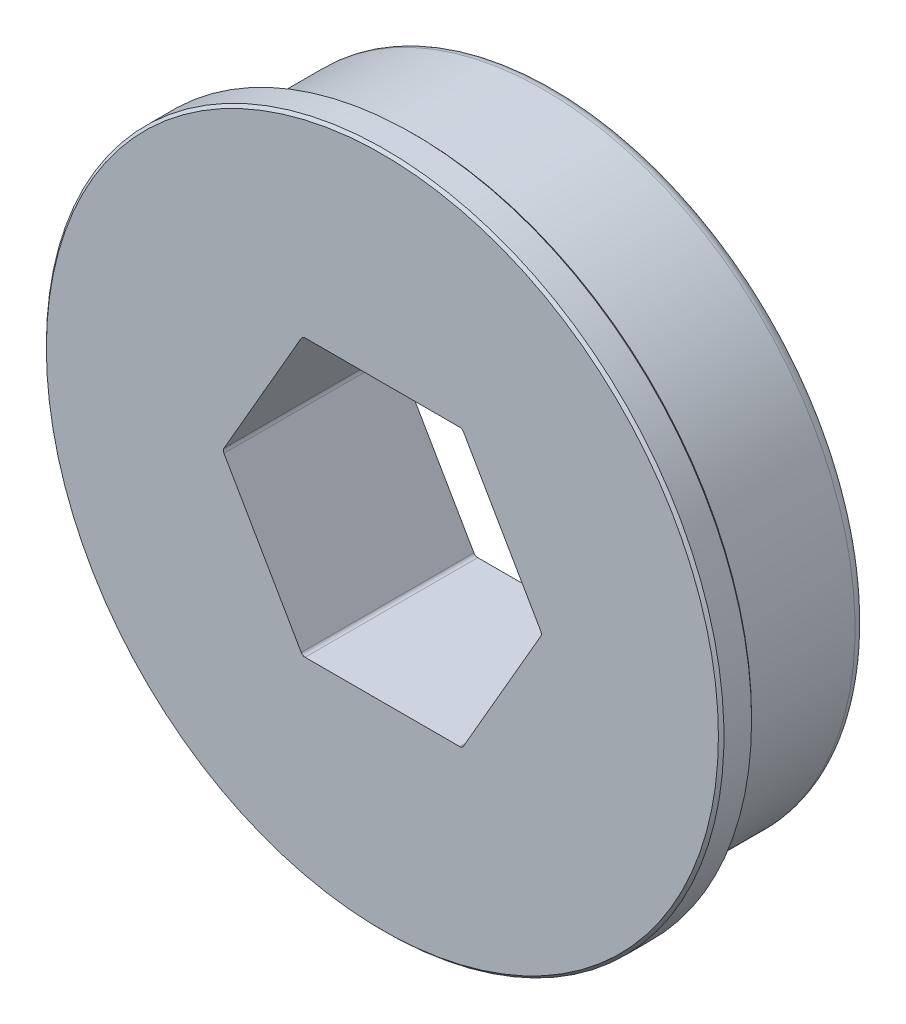
SolidWorks part; units mm, degrees
material "Plain Carbon Steel"
ref_plane "Front Plane" through (0, 0, 0) normal (0, 0, 1) x (1, 0, 0)
ref_plane "Top Plane" through (0, 0, 0) normal (0, 1, 0) x (1, 0, 0)
ref_plane "Right Plane" through (0, 0, 0) normal (1, 0, 0) x (0, 0, -1)
ref_plane "Plane1" through (0, 0, 6.4033) normal (0, 0, -1) x (-1, 0, 0)
sketch "Sketch1" plane through (0, 0, 6.4033) normal (0, 0, -1) x (-1, 0, 0)
  circle A0 centre (0, 0) radius 15.5575
extrude "Boss-Extrude1" add sketch "Sketch1" against normal blind 1.524
sketch "Sketch2" plane through (0, 0, 6.4033) normal (0, 0, -1) x (-1, 0, 0)
  circle A0 centre (0, 0) radius 13.97
extrude "Boss-Extrude2" add sketch "Sketch2" along normal blind 0.508
ref_plane "Plane2" through (0, 0, 5.8953) normal (0, 0, 1) x (1, 0, 0)
sketch "Sketch3" plane through (0, 0, 5.8953) normal (0, 0, 1) x (1, 0, 0)
  circle A0 centre (0, 0) radius 14.2875
extrude "Boss-Extrude3" add sketch "Sketch3" against normal blind 5.8953
sketch "Sketch4" plane through (0, 0, 7.9273) normal (0, 0, 1) x (1, 0, 0)
  line L0 (7.3323, 0) -> (3.6662, 6.35)
  line L1 (3.6662, 6.35) -> (-3.6662, 6.35)
  line L2 (-3.6662, 6.35) -> (-7.3323, 0)
  line L3 (-7.3323, 0) -> (-3.6662, -6.35)
  line L4 (-3.6662, -6.35) -> (3.6662, -6.35)
  line L5 (3.6662, -6.35) -> (7.3323, 0)
extrude "Cut-Extrude1" cut sketch "Sketch4" against normal through all
chamfer "Chamfer1" distance 0.127 angle 45 1 edges at (15.5575, 0, 7.9273)
chamfer "Chamfer2" distance 0.127 angle 45 1 edges at (15.5575, 0, 6.4033)
fillet "Fillet1" radius 0.2032 6 edges at (7.3323, 0, 3.9637) (3.6662, 6.35, 3.9637) (-3.6662, -6.35, 3.9637) (3.6662, -6.35, 3.9637) (-7.3323, 0, 3.9637) (-3.6662, 6.35, 3.9637)
fillet "Fillet2" radius 0.508 1 edges at (-14.2875, 0, 0)
